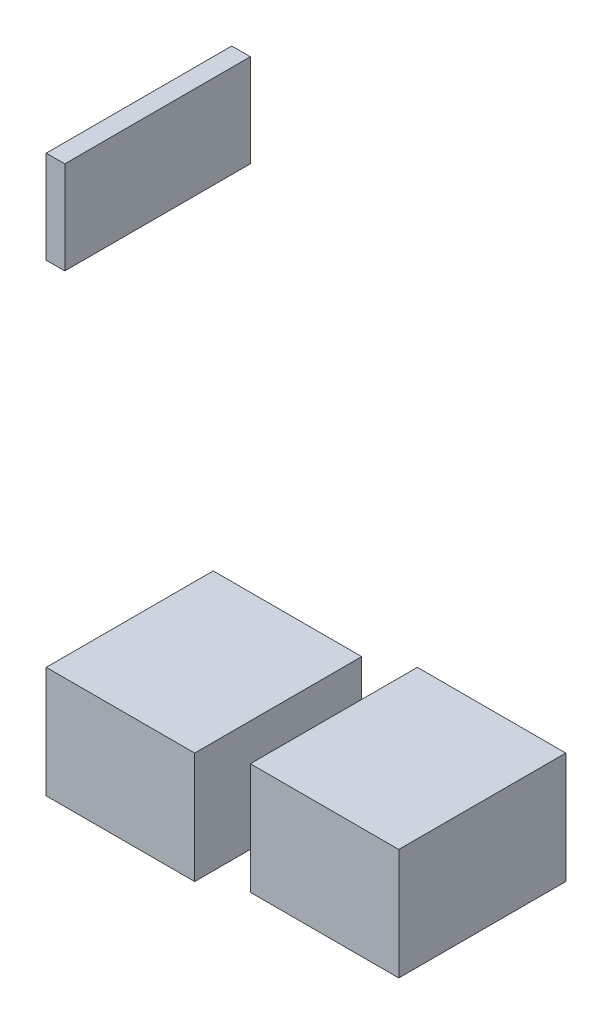
SolidWorks part; units mm, degrees
material "ABS"
ref_plane "Front Plane" through (0, 0, 0) normal (0, 0, 1) x (1, 0, 0)
ref_plane "Top Plane" through (0, 0, 0) normal (0, 1, 0) x (1, 0, 0)
ref_plane "Right Plane" through (0, 0, 0) normal (1, 0, 0) x (0, 0, -1)
ref_plane "Plane2" through (0, -24, 0) normal (0, -1, 0) x (-1, 0, 0)
sketch "Sketch5" plane through (0, -24, 0) normal (0, -1, 0) x (-1, 0, 0)
  line L0 (-8, -10) -> (0, -10)
  line L1 (0, -10) -> (0, -1)
  line L2 (0, -1) -> (-8, -1)
  line L3 (-8, -1) -> (-8, -10)
extrude "Boss-Extrude2" add sketch "Sketch5" against normal blind 6 separate body
ref_plane "Plane3" through (0, -18, 0) normal (0, 1, 0) x (1, 0, 0)
sketch "Sketch10" plane through (0, -18, 0) normal (0, 1, 0) x (1, 0, 0)
  line L0 (18, 0) -> (10, 0)
  line L1 (10, 0) -> (10, -9)
  line L2 (10, -9) -> (18, -9)
  line L3 (18, -9) -> (18, 0)
extrude "Boss-Extrude3" add sketch "Sketch10" against normal blind 6 separate body
sketch "Sketch11" plane through (10, 0, 0) normal (-1, 0, 0) x (0, 0, 1)
  line L0 (8.25, -21) -> (6.625, -18.1854)
  line L1 (6.625, -18.1854) -> (3.375, -18.1854)
  line L2 (3.375, -18.1854) -> (1.75, -21)
  line L3 (1.75, -21) -> (3.375, -23.8146)
  line L4 (3.375, -23.8146) -> (6.625, -23.8146)
  line L5 (6.625, -23.8146) -> (8.25, -21)
extrude "Cut-Extrude1" cut sketch "Sketch11" against normal blind 2
ref_plane "Plane4" through (0, 0, 0) normal (0, 0, -1) x (-1, 0, 0)
sketch "Sketch17" plane through (0, 0, 0) normal (0, 0, -1) x (-1, 0, 0)
  line L0 (-7.8571, 6) -> (-7.8571, 1)
  line L1 (-7.8571, 1) -> (-10.2857, 1)
  line L2 (-10.2857, 1) -> (-10.2857, 6)
  line L3 (-10.2857, 6) -> (-11.2857, 6)
  line L4 (-11.2857, 6) -> (-11.2857, 1)
  line L5 (-11.2857, 1) -> (-13.7143, 1)
  line L6 (-13.7143, 1) -> (-13.7143, 6)
  line L7 (-13.7143, 6) -> (-14.7143, 6)
  line L8 (-14.7143, 6) -> (-14.7143, 1)
  line L9 (-14.7143, 1) -> (-17.1429, 1)
  line L10 (-17.1429, 1) -> (-17.1429, 6)
  line L11 (-17.1429, 6) -> (-18.1429, 6)
  line L12 (-18.1429, 6) -> (-18.1429, 1)
  line L13 (-18.1429, 1) -> (-20.5714, 1)
  line L14 (-20.5714, 1) -> (-20.5714, 6)
  line L15 (-20.5714, 6) -> (-21.5714, 6)
  line L16 (-21.5714, 6) -> (-21.5714, 1)
  line L17 (-21.5714, 1) -> (-24, 1)
  line L18 (-24, 1) -> (-24, 6)
  line L19 (-24, 6) -> (-25, 6)
  line L20 (-25, 6) -> (-25, 0)
  line L21 (-25, 0) -> (0, 0)
  line L22 (0, 0) -> (0, 6)
  line L23 (0, 6) -> (-1, 6)
  line L24 (-1, 6) -> (-1, 1)
  line L25 (-1, 1) -> (-3.4286, 1)
  line L26 (-3.4286, 1) -> (-3.4286, 6)
  line L27 (-3.4286, 6) -> (-4.4286, 6)
  line L28 (-4.4286, 6) -> (-4.4286, 1)
  line L29 (-4.4286, 1) -> (-6.8571, 1)
  line L30 (-6.8571, 1) -> (-6.8571, 6)
  line L31 (-6.8571, 6) -> (-7.8571, 6)
  line L32 (0, 1) -> (-25, 1)
extrude "Boss-Extrude4" add sketch "Sketch17" against normal blind 10 separate body contours L32 L22 L23 L24
